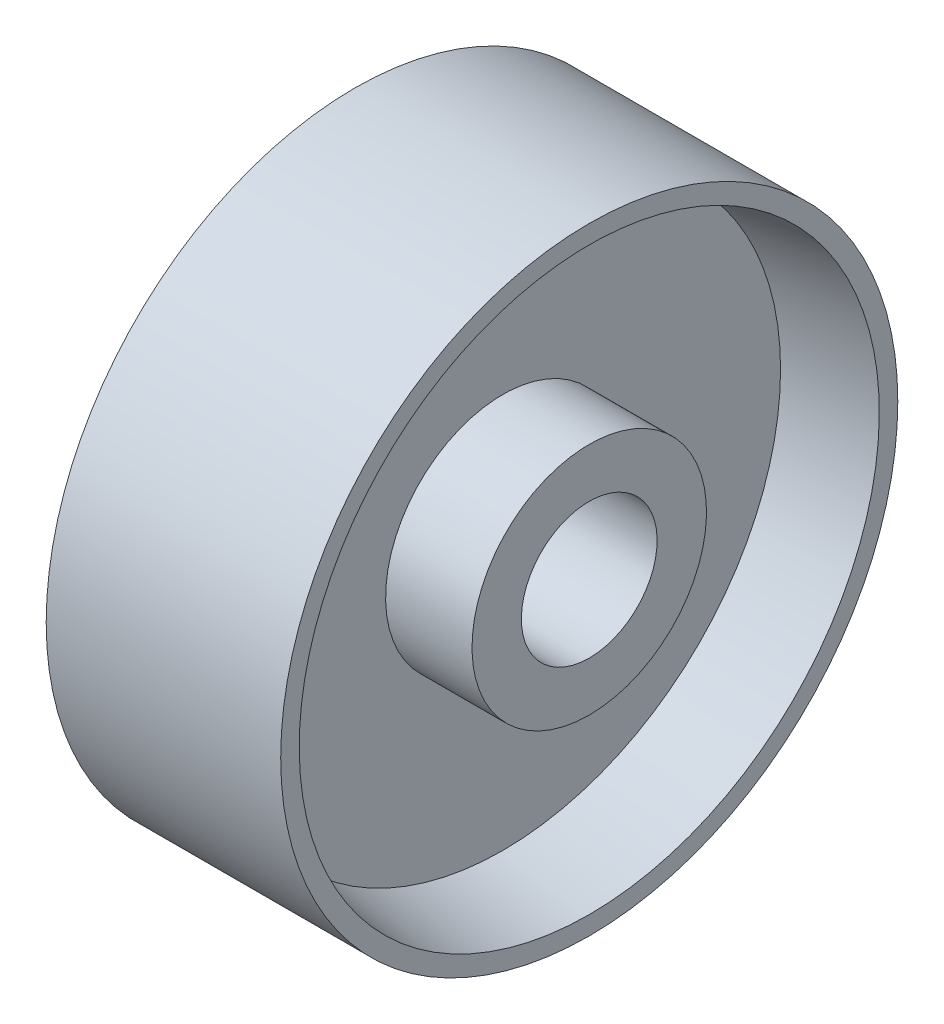
SolidWorks part; units mm, degrees
ref_plane "Plan de face" through (0, 0, 0) normal (0, 0, 1) x (1, 0, 0)
ref_plane "Plan de dessus" through (0, 0, 0) normal (0, 1, 0) x (1, 0, 0)
ref_plane "Plan de droite" through (0, 0, 0) normal (1, 0, 0) x (0, 0, -1)
sketch "Esquisse1" plane through (0, 0, 0) normal (0, 0, 1) x (1, 0, 0)
  line L0 (-25, 0) -> (25, 0) construction
  line L1 (19, -11) -> (-19, -11)
  line L2 (-19, -11) -> (-19, -19)
  line L3 (-19, -19) -> (-5, -19)
  line L4 (-5, -19) -> (-5, -45)
  line L5 (-5, -45) -> (-19, -47)
  line L6 (-19, -47) -> (-19, -50)
  line L7 (-19, -50) -> (19, -50)
  line L8 (19, -50) -> (19, -47)
  line L9 (19, -47) -> (5, -45)
  line L10 (5, -45) -> (5, -19)
  line L11 (5, -19) -> (19, -19)
  line L12 (19, -19) -> (19, -11)
  point P2 (0, 0)
  point P29 (0, -50)
  dimension "D1" = 50
  dimension "D2" = 11
  dimension "D3" = 19
  dimension "D4" = 10
  dimension "D5" = 5
  dimension "D6" = 38
  dimension "D7" = 3
  dimension "D8" = 5
  dimension "D9" = 50
revolve "Révolution1" add sketch "Esquisse1" angle 360 about L0
